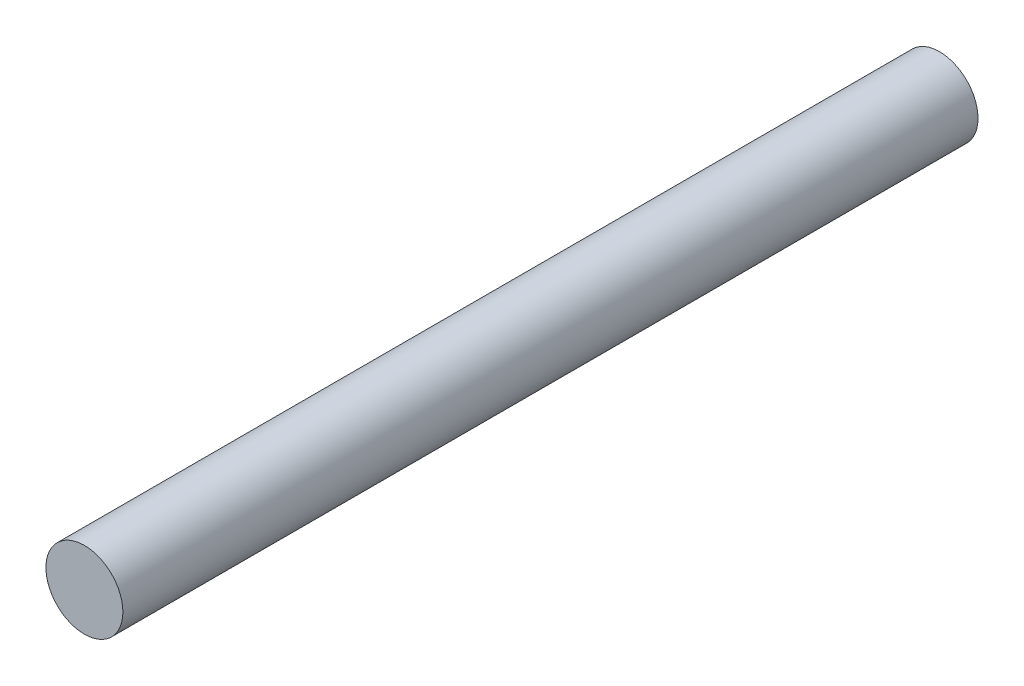
SolidWorks part; units mm, degrees
ref_plane "Front Plane" through (0, 0, 0) normal (0, 0, 1) x (1, 0, 0)
ref_plane "Top Plane" through (0, 0, 0) normal (0, 1, 0) x (1, 0, 0)
ref_plane "Right Plane" through (0, 0, 0) normal (1, 0, 0) x (0, 0, -1)
sketch "Sketch1" plane through (0, 0, 0) normal (0, 0, 1) x (1, 0, 0)
  circle A0 centre (0, 0) radius 1.8
  dimension "D1" = 3.6
extrude "Boss-Extrude1" add sketch "Sketch1" along normal blind 40
